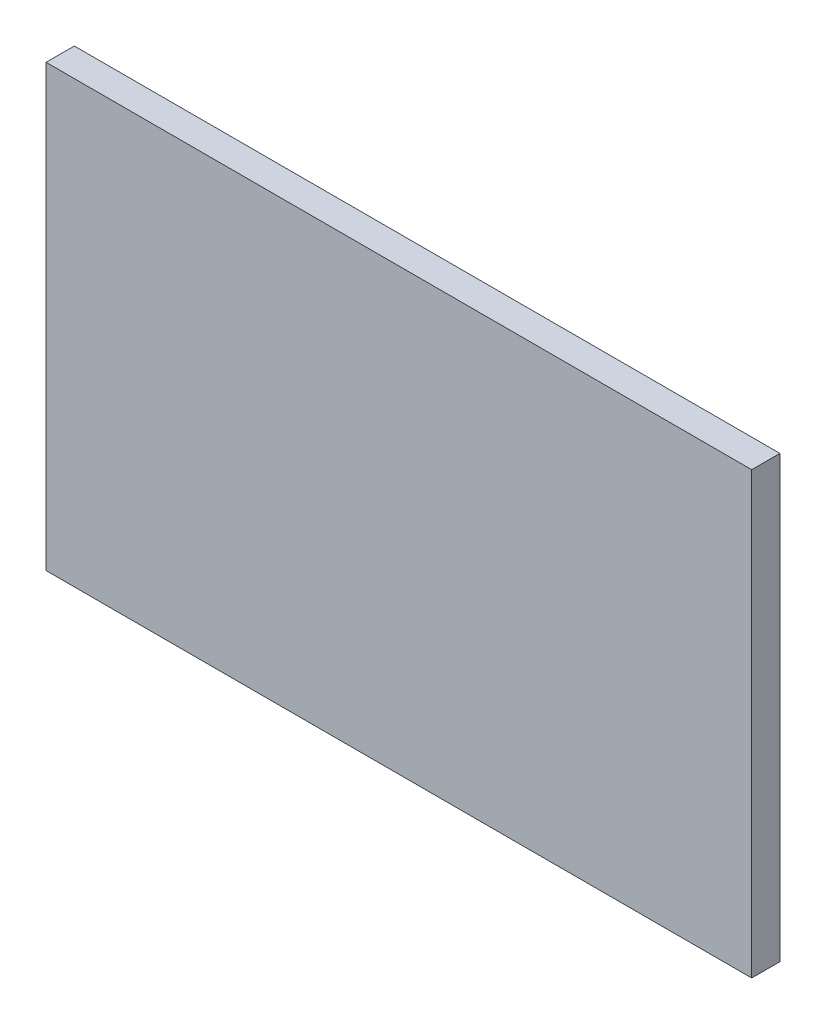
SolidWorks part; units mm, degrees
ref_plane "Front Plane" through (0, 0, 0) normal (0, 0, 1) x (1, 0, 0)
ref_plane "Top Plane" through (0, 0, 0) normal (0, 1, 0) x (1, 0, 0)
ref_plane "Right Plane" through (0, 0, 0) normal (1, 0, 0) x (0, 0, -1)
sketch "Sketch1" plane through (0, 0, 110.5163) normal (0, 0, 1) x (1, 0, 0)
  line L1 (2.9392, 73.2166) -> (102.9392, 73.2166)
  line L2 (2.9392, 73.2166) -> (2.9392, 10.8313)
  line L3 (2.9392, 10.8313) -> (102.9392, 10.8313)
  line L4 (102.9392, 73.2166) -> (102.9392, 10.8313)
extrude "Boss-Extrude1" add sketch "Sketch1" along normal blind 4
